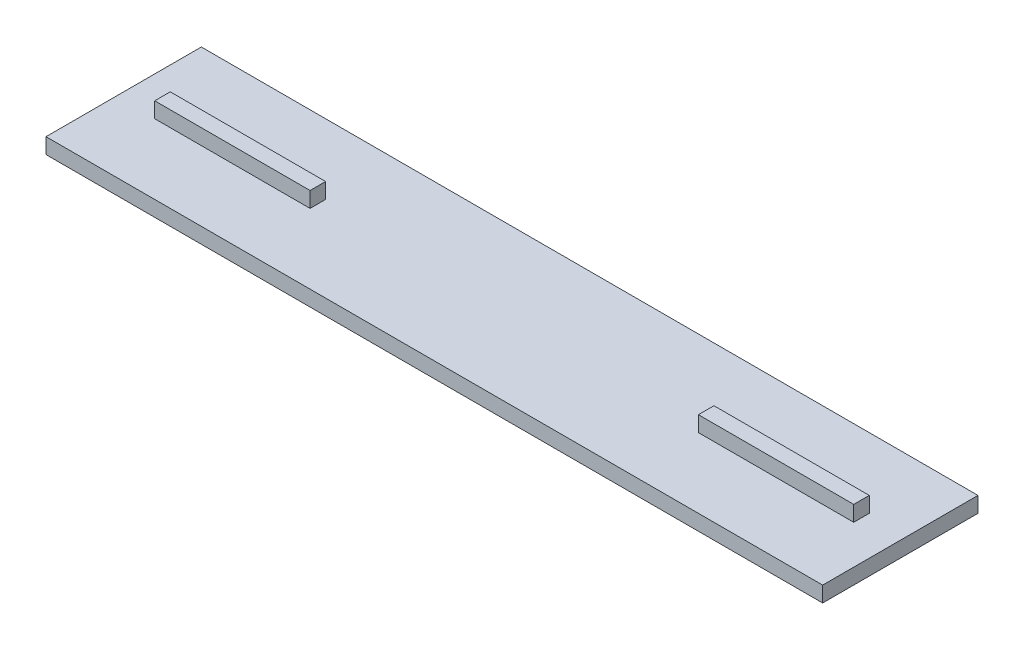
SolidWorks part; units mm, degrees
ref_plane "Front Plane" through (0, 0, 0) normal (0, 0, 1) x (1, 0, 0)
ref_plane "Top Plane" through (0, 0, 0) normal (0, 1, 0) x (1, 0, 0)
ref_plane "Right Plane" through (0, 0, 0) normal (1, 0, 0) x (0, 0, -1)
sketch "Sketch1" plane through (0, 0, 0) normal (0, 1, 0) x (1, 0, 0)
  line L0 (50, 0) -> (-50, 0)
  line L1 (-50, 0) -> (-50, -20)
  line L2 (-50, -20) -> (50, -20)
  line L3 (0, -55) -> (0, 55) construction
  line L4 (50, 0) -> (50, -20)
  point P8 (0, -20)
  point P9 (0, 0)
  dimension "D1" = 50
  dimension "D2" = 20
extrude "Boss-Extrude1" add sketch "Sketch1" along normal blind 2
sketch "Sketch2" plane through (0, 0, 0) normal (0, 1, 0) x (1, 0, 0)
  line L0 (0, 0) -> (0, -20) construction
  line L1 (-50, -20) -> (50, -20) construction
  line L2 (0, -10) -> (-45, -10) construction
  line L3 (-45, -10) -> (-45, -11)
  line L4 (-45, -11) -> (-25, -11)
  line L5 (-45, -10) -> (-45, -9)
  line L6 (-45, -9) -> (-25, -9)
  line L7 (-25, -9) -> (-25, -11)
  line L8 (0, -1.1) -> (0, 1.1) construction
  line L9 (45, -10) -> (45, -9)
  line L10 (45, -10) -> (45, -11)
  line L11 (45, -11) -> (25, -11)
  line L12 (25, -9) -> (25, -11)
  line L13 (45, -9) -> (25, -9)
  dimension "D1" = 45
  dimension "D2" = 1
  dimension "D3" = 20
  dimension "D4" = 1
extrude "Boss-Extrude2" add sketch "Sketch2" along normal blind 4
